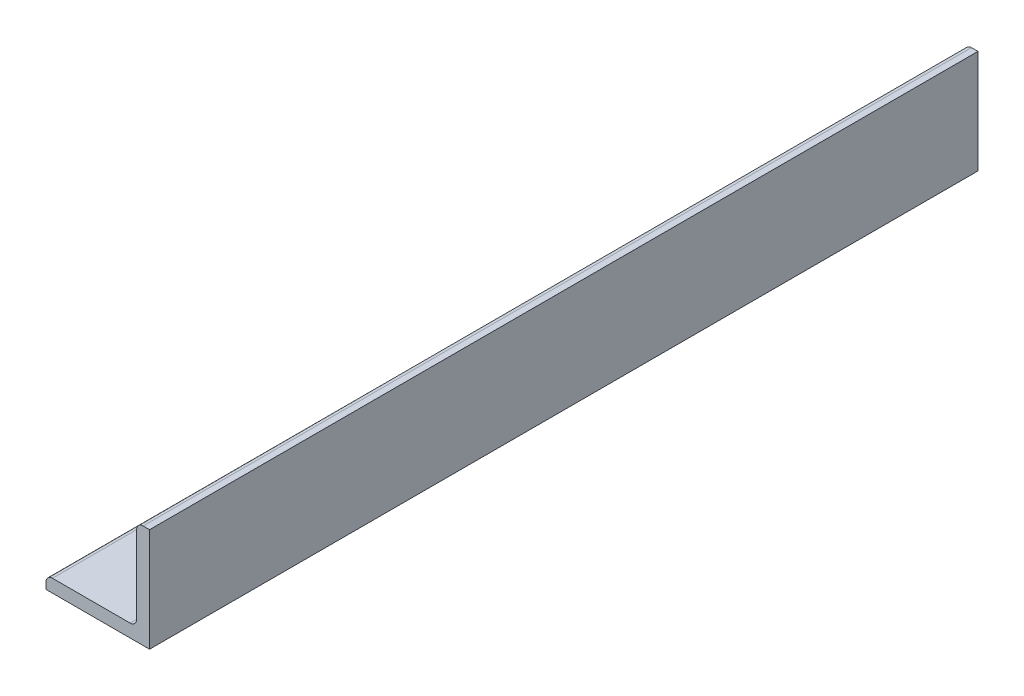
SolidWorks part; units mm, degrees
ref_plane "Front Plane" through (0, 0, 0) normal (0, 0, 1) x (1, 0, 0)
ref_plane "Top Plane" through (0, 0, 0) normal (0, 1, 0) x (1, 0, 0)
ref_plane "Right Plane" through (0, 0, 0) normal (1, 0, 0) x (0, 0, -1)
sketch "Sketch2" plane through (0, 0, 0) normal (0, 0, 1) x (1, 0, 0)
  line L0 (-12.7, 0) -> (12.7, 0)
  line L1 (12.7, 0) -> (12.7, 25.4)
  line L2 (12.7, 25.4) -> (9.525, 25.4) construction
  line L3 (9.525, 23.8125) -> (9.525, 4.7625)
  line L4 (7.9375, 3.175) -> (-11.1125, 3.175)
  line L5 (-12.7, 0) -> (-12.7, 3.175) construction
  line L6 (11.1125, 25.4) -> (12.7, 25.4)
  line L7 (-12.7, 1.5875) -> (-12.7, 0)
  arc A0 (9.525, 23.8125) -> (11.1125, 25.4) centre (11.1125, 23.8125) cw
  arc A1 (-12.7, 1.5875) -> (-11.1125, 3.175) centre (-11.1125, 1.5875) cw
  arc A2 (9.525, 4.7625) -> (7.9375, 3.175) centre (7.9375, 4.7625) cw
  dimension "Vert" = 25.4
  dimension "Horz" = 25.4
  dimension "Thickness" = 3.175
extrude "Boss-Extrude1" add sketch "Sketch2" along normal mid plane 203.2
ref_plane "Contact Plane 1" through (0, 3.175, 0) normal (0, 1, 0) x (1, 0, 0)
ref_plane "Contact Plane 2" through (9.525, 0, 0) normal (-1, 0, 0) x (0, 0, 1)
